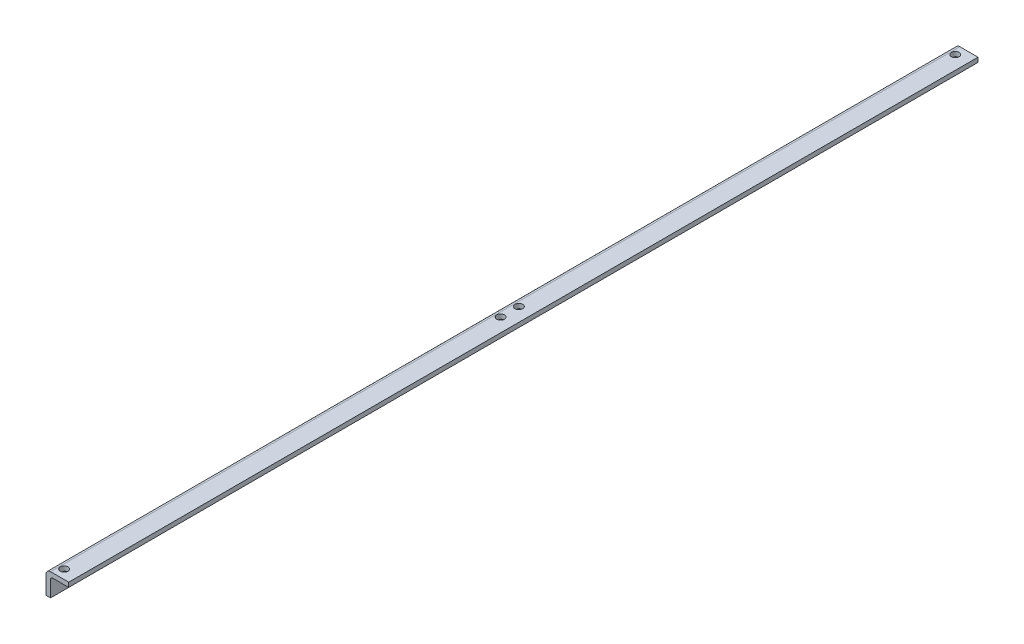
SolidWorks part; units mm, degrees
ref_plane "Спереди" through (0, 0, 0) normal (0, 0, 1) x (1, 0, 0)
ref_plane "Сверху" through (0, 0, 0) normal (0, 1, 0) x (1, 0, 0)
ref_plane "Справа" through (0, 0, 0) normal (1, 0, 0) x (0, 0, -1)
sketch "Эскиз1" plane through (0, 0, 0) normal (0, 0, 1) x (1, 0, 0)
  line L1 (0, 0) -> (2, 0)
  line L2 (0, 0) -> (0, 8)
  line L3 (2, 10) -> (10, 10)
  line L4 (10, 8) -> (10, 10)
  line L6 (2, 0) -> (2, 7)
  line L7 (3, 8) -> (10, 8)
  arc A0 (0, 8) -> (2, 10) centre (2, 8) cw
  arc A1 (3, 8) -> (2, 7) centre (3, 7) ccw
  point P8 (0, 10)
  dimension "D5" = 2
  dimension "D6" = 2
  dimension "D1" = 10
  dimension "D2" = 10
  dimension "D3" = 2
  dimension "D4" = 2
extrude "Вытянуть1" add sketch "Эскиз1" along normal blind 400
sketch "Эскиз2" plane through (0, 10, 0) normal (0, 1, 0) x (-1, 0, 0)
  line L0 (-4, 405.0815) -> (-4, 316.8769) construction
  line L1 (-10, 400) -> (-10, 0) construction
  line L2 (-10, 400) -> (-2, 400) construction
  line L3 (61.9571, 200) -> (-49.6218, 200) construction
  line L4 (-10, 0) -> (-2, 0) construction
  line L5 (58.8016, 300) -> (-34.5998, 300) construction
  circle A0 centre (-4, 396) radius 1.7
  circle A1 centre (-4, 4) radius 1.7
  circle A2 centre (-4, 204) radius 1.7
  circle A3 centre (-4, 196) radius 1.7
  dimension "D3" = 3.4
  dimension "D4" = 96
  dimension "D1" = 6
  dimension "D2" = 4
extrude "Вырез-Вытянуть1" cut sketch "Эскиз2" against normal blind 5
sketch "Эскиз3" plane through (0, 0, 0) normal (-1, 0, 0) x (0, 0, 1)
  line L0 (410.7046, 4) -> (245.2957, 4) construction
  line L3 (400, 0) -> (0, 0) construction
  line L4 (400, 8) -> (400, 0) construction
  line L5 (200, -9.7117) -> (200, 15.8346) construction
  line L6 (0, 8) -> (0, 0) construction
  circle A0 centre (388, 4) radius 1.7
  circle A1 centre (380, 4) radius 1.7
  circle A2 centre (20, 4) radius 1.7
  circle A3 centre (12, 4) radius 1.7
  dimension "D2" = 8
  dimension "D4" = 3.4
  dimension "D1" = 4
  dimension "D3" = 12
extrude "Вырез-Вытянуть2" cut sketch "Эскиз3" against normal blind 5
